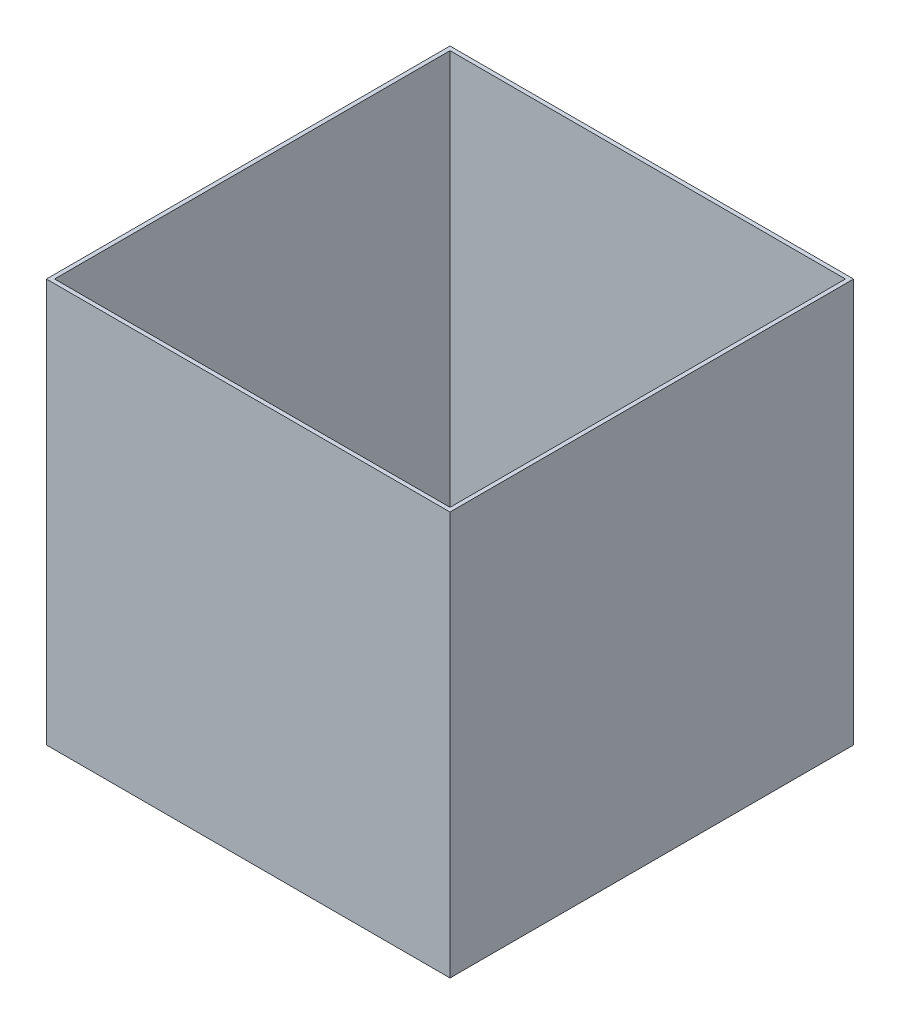
SolidWorks part; units mm, degrees
ref_plane "前视基准面" through (0, 0, 0) normal (0, 0, 1) x (1, 0, 0)
ref_plane "上视基准面" through (0, 0, 0) normal (0, 1, 0) x (1, 0, 0)
ref_plane "右视基准面" through (0, 0, 0) normal (1, 0, 0) x (0, 0, -1)
sketch "草图1" plane through (0, 0, 0) normal (0, 1, 0) x (1, 0, 0)
  line L1 (0, 0) -> (-200, 0)
  line L2 (0, 0) -> (0, 200)
  line L3 (0, 200) -> (-200, 200)
  line L4 (-200, 0) -> (-200, 200)
  line L5 (-198, 198) -> (-2, 198)
  line L6 (-198, 198) -> (-198, 2)
  line L7 (-198, 2) -> (-2, 2)
  line L8 (-2, 198) -> (-2, 2)
  dimension "D1" = 200
  dimension "D2" = 200
  dimension "D3" = 196
  dimension "D4" = 196
  dimension "D5" = 2
  dimension "D6" = 2
extrude "凸台-拉伸1" add sketch "草图1" along normal blind 200
